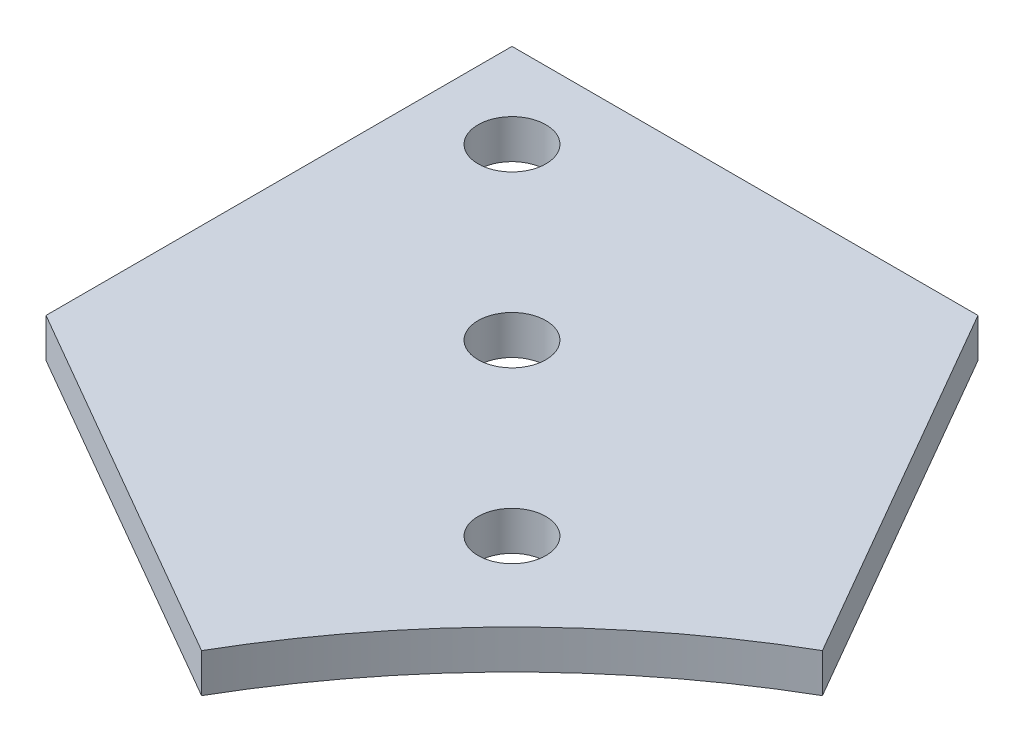
SolidWorks part; units mm, degrees
ref_plane "Front Plane" through (0, 0, 0) normal (0, 0, 1) x (1, 0, 0)
ref_plane "Top Plane" through (0, 0, 0) normal (0, 1, 0) x (1, 0, 0)
ref_plane "Right Plane" through (0, 0, 0) normal (1, 0, 0) x (0, 0, -1)
sketch "constraints" plane through (0, 0, 0) normal (0, 1, 0) x (1, 0, 0)
  line L0 (0, 0) -> (-37.5278, 65) construction
  line L1 (-65, -65) -> (65, -65) construction
  line L2 (-65, -65) -> (-65, 65) construction
  line L3 (-65, 65) -> (65, 65) construction
  line L4 (65, -65) -> (65, 65) construction
  line L5 (-65, -65) -> (65, 65) construction
  line L6 (-65, 65) -> (65, -65) construction
  line L7 (0, 0) -> (-65, 37.5278) construction
  circle A0 centre (0, 0) radius 50 construction
  point P0 (0, 0)
  point P8 (-60, 60)
  point P9 (-50, 50)
  point P10 (-40, 40)
  point P11 (-25, 43.3013)
  point P14 (-43.3013, 25)
  dimension "D3" = 100
  dimension "D1" = 130
  dimension "D2" = 130
  dimension "D4" = 60
  dimension "D5" = 50
  dimension "D6" = 40
  dimension "D7" = 15
  dimension "D8" = 15
sketch "Sketch3" plane through (0, 0, 0) normal (0, 1, 0) x (1, 0, 0)
  line L6 (-65, 65) -> (-37.5278, 65)
  line L7 (-37.5278, 65) -> (-25, 43.3013)
  line L8 (-25, 43.3013) -> (-43.3013, 25)
  line L9 (-43.3013, 25) -> (-65, 37.5278)
  line L10 (-65, 37.5278) -> (-65, 65)
extrude "Boss-Extrude1" add sketch "Sketch3" along normal blind 2.3
sketch "Sketch4" plane through (0, 2.3, 0) normal (0, 1, 0) x (1, 0, 0)
  line L0 (-65, -65) -> (65, 65) construction
  circle A0 centre (-60, 60) radius 2
  circle A1 centre (-50, 50) radius 2
  circle A2 centre (-40, 40) radius 2
  circle A3 centre (0, 0) radius 50
  dimension "D1" = 4
  dimension "D2" = 100
extrude "Cut-Extrude1" cut sketch "Sketch4" against normal through all
